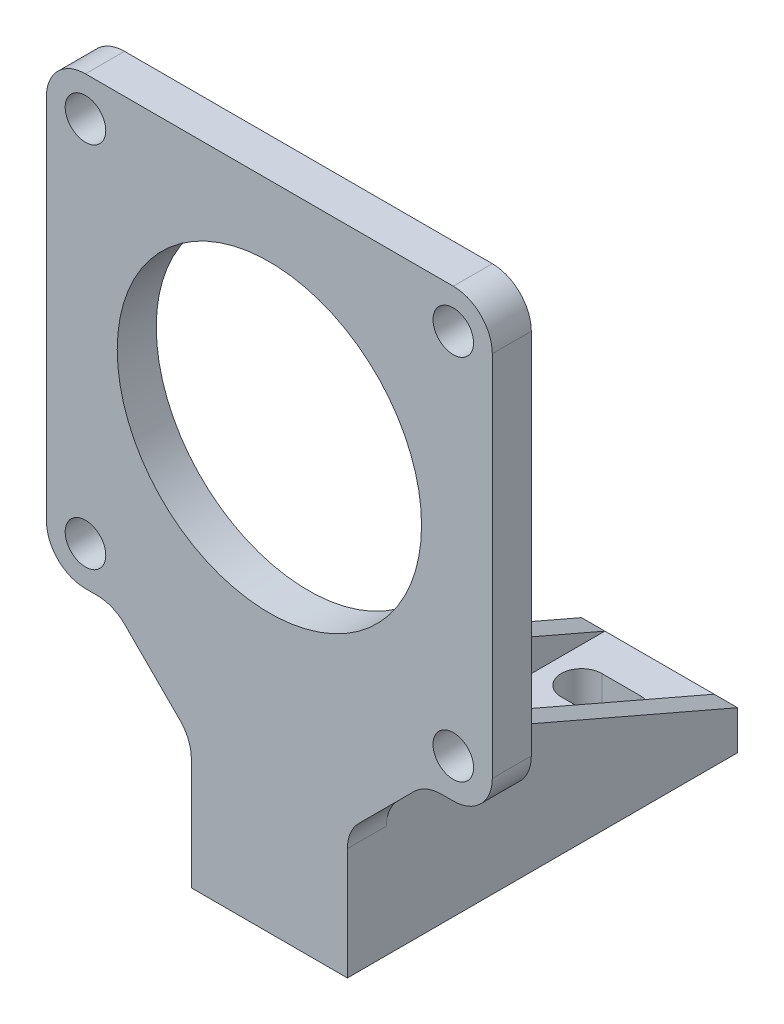
SolidWorks part; units mm, degrees
ref_plane "Front Plane" through (0, 0, 0) normal (0, 0, 1) x (1, 0, 0)
ref_plane "Top Plane" through (0, 0, 0) normal (0, 1, 0) x (1, 0, 0)
ref_plane "Right Plane" through (0, 0, 0) normal (1, 0, 0) x (0, 0, -1)
sketch "Sketch1" plane through (0, 0, 0) normal (0, 0, 1) x (1, 0, 0)
  line L0 (0, -55) -> (0, -28.57) construction
  line L1 (-23.57, 23.57) -> (23.57, 23.57) construction
  line L2 (-23.57, 23.57) -> (-23.57, -23.57) construction
  line L3 (-23.57, -23.57) -> (23.57, -23.57) construction
  line L4 (23.57, 23.57) -> (23.57, -23.57) construction
  line L5 (-23.57, 23.57) -> (23.57, -23.57) construction
  line L6 (-23.57, -23.57) -> (23.57, 23.57) construction
  line L7 (-28.57, 28.57) -> (28.57, 28.57)
  line L8 (-28.57, 28.57) -> (-28.57, -28.57)
  line L9 (-28.57, -28.57) -> (28.57, -28.57)
  line L10 (28.57, 28.57) -> (28.57, -28.57)
  line L11 (-28.57, 28.57) -> (28.57, -28.57) construction
  line L12 (-28.57, -28.57) -> (28.57, 28.57) construction
  line L13 (-10, -28.57) -> (10, -28.57)
  line L14 (-10, -28.57) -> (-10, -55)
  line L15 (-10, -55) -> (10, -55)
  line L16 (10, -28.57) -> (10, -55)
  circle A0 centre (-23.57, 23.57) radius 2.6
  circle A1 centre (23.57, 23.57) radius 2.6
  circle A2 centre (23.57, -23.57) radius 2.6
  circle A3 centre (-23.57, -23.57) radius 2.6
  circle A4 centre (0, 0) radius 19.5
  point P0 (0, 0)
  point P10 (0, 0)
  dimension "D2" = 5.2
  dimension "D3" = 5
  dimension "D5" = 39
  dimension "D1" = 47.14
  dimension "D4" = 5
  dimension "D6" = 20
  dimension "D7" = 26.43
extrude "Boss-Extrude1" add sketch "Sketch1" along normal blind 5 contours L10 L7 L8 L9 A4 A3 A2 A1 A0 | L16 L9 L14 L15
sketch "Sketch3" plane through (10, 0, 0) normal (1, 0, 0) x (0, 0, -1)
  line L0 (0, -28.57) -> (0, -55) construction
  line L1 (0, -50) -> (45, -50)
  line L2 (0, -50) -> (0, -55)
  line L3 (0, -55) -> (45, -55)
  line L4 (45, -50) -> (45, -55)
  line L5 (-5, -55) -> (0, -55) construction
  dimension "D1" = 45
  dimension "D2" = 5
extrude "Boss-Extrude2" add sketch "Sketch3" against normal up to surface (20 mm away) up to face at (-10, -41.785, 2.5)
sketch "Sketch5" plane through (10, 0, 0) normal (1, 0, 0) x (0, 0, -1)
  line L0 (0, -35) -> (15, -50)
  line L1 (0, -28.57) -> (0, -50) construction
  line L2 (45, -50) -> (0, -50) construction
  line L3 (15, -50) -> (0, -50)
  line L4 (0, -50) -> (0, -35)
  dimension "D1" = 45
  dimension "D2" = 15
extrude "Boss-Extrude3" add sketch "Sketch5" against normal blind 5 from offset 7.5 offset against normal yes
sketch "Sketch4" plane through (0, -50, 0) normal (0, 1, 0) x (1, 0, 0)
  line L0 (-2.5, 37.5) -> (2.5, 37.5) construction
  line L1 (-2.5, 40.1) -> (2.5, 40.1)
  line L2 (-2.5, 34.9) -> (2.5, 34.9)
  line L3 (-2.5, 22.5) -> (2.5, 22.5) construction
  line L4 (-2.5, 25.1) -> (2.5, 25.1)
  line L5 (-2.5, 19.9) -> (2.5, 19.9)
  line L6 (-10, 45) -> (10, 45) construction
  arc A0 (-2.5, 40.1) -> (-2.5, 34.9) centre (-2.5, 37.5) ccw
  arc A1 (2.5, 34.9) -> (2.5, 40.1) centre (2.5, 37.5) ccw
  arc A2 (-2.5, 25.1) -> (-2.5, 19.9) centre (-2.5, 22.5) ccw
  arc A3 (2.5, 19.9) -> (2.5, 25.1) centre (2.5, 22.5) ccw
  point P2 (0, 37.5)
  point P7 (0, 22.5)
  dimension "D1" = 5.2
  dimension "D2" = 7.5
  dimension "D3" = 15
  dimension "D4" = 5
extrude "Cut-Extrude1" cut sketch "Sketch4" against normal up to next
fillet "Fillet1" radius 5 4 edges at (-28.57, -28.57, 2.5) (-28.57, 28.57, 2.5) (28.57, 28.57, 2.5) (28.57, -28.57, 2.5)
chamfer "Chamfer1" distance 4 angle 45 2 edges at (-6.25, -50, 0) (6.25, -50, 0)
chamfer "Chamfer2" distance 10 angle 45 2 edges at (-10, -28.57, 2.5) (10, -28.57, 2.5)
fillet "Fillet2" radius 5 4 edges at (-10, -38.57, 2.5) (-20, -28.57, 2.5) (10, -38.57, 2.5) (20, -28.57, 2.5)
sketch "Sketch6" plane through (10, 0, 0) normal (1, 0, 0) x (0, 0, -1)
  line L2 (45, -50) -> (4, -50)
  line L3 (4, -50) -> (0, -46)
  line L5 (45, -50) -> (0, -30.5345)
  line L6 (0, 23.57) -> (0, -23.57) construction
  line L7 (0, -30.5345) -> (0, -46)
  line L9 (0, -30.0345) -> (-5, -30.0345) construction
  point P0 (0, -32.6832)
  dimension "D1" = 0.5
extrude "Boss-Extrude4" add sketch "Sketch6" against normal blind 3
mirror "Mirror1" about plane through (0, 0, 0) normal (1, 0, 0) of "Boss-Extrude4"
